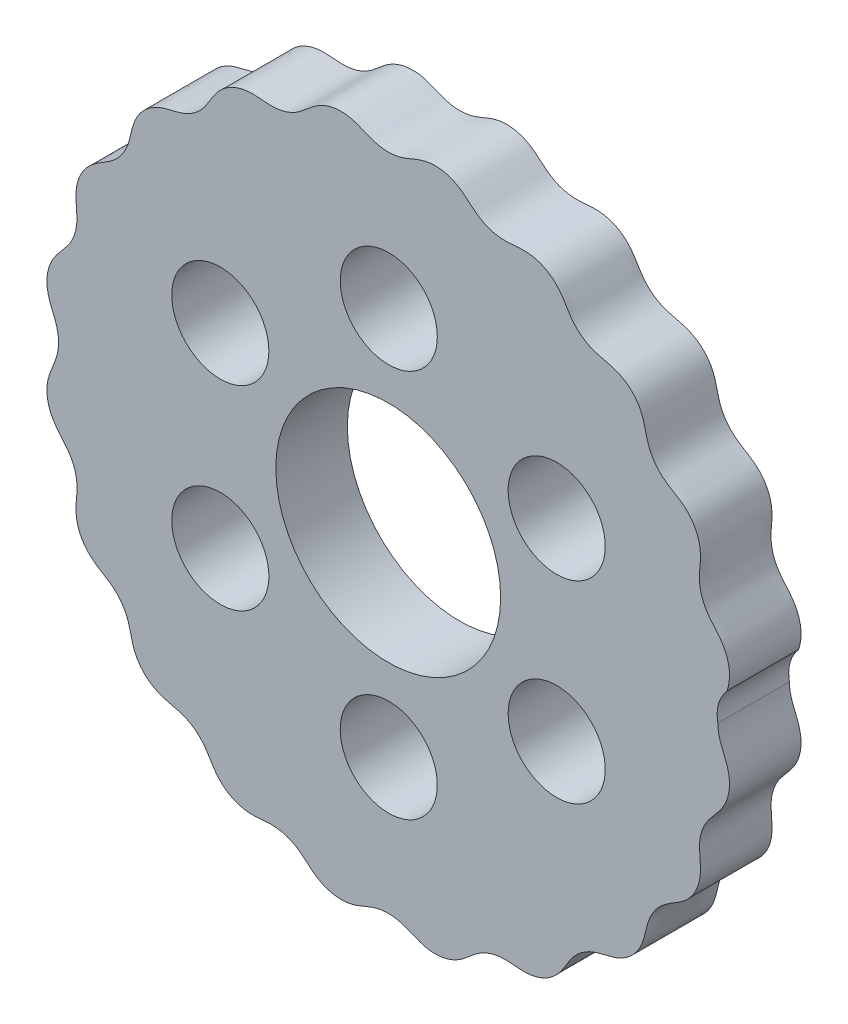
SolidWorks part; units mm, degrees
ref_plane "Front Plane" through (0, 0, 0) normal (0, 0, 1) x (1, 0, 0)
ref_plane "Top Plane" through (0, 0, 0) normal (0, 1, 0) x (1, 0, 0)
ref_plane "Right Plane" through (0, 0, 0) normal (1, 0, 0) x (0, 0, -1)
sketch "Sketch1" plane through (0, 0, 0) normal (0, 0, 1) x (1, 0, 0)
  spline S0 degree 4 poles (28.4232, 17.0994) (28.5775, 16.9984) (28.8791, 16.7867) (29.3025, 16.4267) (29.7783, 15.8595) (30.1762, 15.1774) (30.4555, 14.3878) (30.5822, 13.508) (30.5259, 12.5781) (30.4267, 11.6947) (30.4524, 10.841) (30.6166, 10.0442) (30.9061, 9.3262) (31.3279, 8.6403) (31.865, 8.0014) (32.4465, 7.3605) (32.9398, 6.604) (33.2503, 5.8126) (33.3942, 5.0292) (33.3985, 4.2869) (33.3069, 3.6905) (33.1661, 3.1943) (33.0172, 2.7916) (32.8858, 2.4743) (32.7509, 2.1586) (32.6212, 1.8407) (32.5187, 1.5581) (32.4421, 1.3122) (32.3869, 1.1049) (32.3484, 0.9372) (32.3158, 0.7683) (32.2895, 0.6004) (32.2695, 0.4318) (32.2562, 0.2498) (32.2495, 0.0634) (32.2494, -0.061) (32.2559, -0.2448) (32.2689, -0.4242) (32.2881, -0.5903) (32.3136, -0.7553) (32.3451, -0.9213) (32.3823, -1.0862) (32.4357, -1.2902) (32.51, -1.5322) (32.6096, -1.8103) (32.736, -2.1232) (32.8684, -2.4336) (32.9985, -2.745) (33.1477, -3.1396) (33.292, -3.6256) (33.3912, -4.2099) (33.4016, -4.9639) (33.2631, -5.784) (32.9336, -6.633) (32.3807, -7.4491) (31.7436, -8.1285) (31.1946, -8.8249) (30.792, -9.5638) (30.5426, -10.3176) (30.4261, -11.151) (30.4537, -12.0374) (30.5715, -12.9614) (30.549, -13.9461) (30.3058, -14.909) (29.8489, -15.7949) (29.1976, -16.5596) (28.3876, -17.1561) (27.551, -17.6113) (26.8095, -18.1374) (26.2056, -18.754) (25.7542, -19.4331) (25.4191, -20.211) (25.2057, -21.0593) (25.0232, -21.9462) (24.6789, -22.8243) (24.1554, -23.6109) (23.4726, -24.2662) (22.6632, -24.7596) (21.7674, -25.069) (20.8739, -25.2417) (20.0262, -25.4836) (19.258, -25.8528) (18.597, -26.3393) (18.0153, -26.9624) (17.5302, -27.6979) (17.088, -28.4937) (16.5078, -29.2435) (15.7729, -29.8593) (14.9126, -30.3026) (13.9653, -30.5464) (12.9803, -30.573) (12.0563, -30.4559) (11.17, -30.4252) (10.3361, -30.5384) (9.5813, -30.7844) (8.8407, -31.184) (8.1424, -31.7308) (7.4636, -32.3685) (6.65, -32.9246) (5.7398, -33.2826) (4.783, -33.428) (3.8265, -33.3603) (2.917, -33.0932) (2.0916, -32.709) (1.2664, -32.4001) (0.4293, -32.2392) (-0.3914, -32.2356) (-1.2297, -32.3897) (-2.0572, -32.6933) (-2.8817, -33.0786) (-3.7888, -33.3534) (-4.7338, -33.4284) (-5.6711, -33.298) (-6.5564, -32.9679) (-7.3502, -32.4586) (-8.0187, -31.8479) (-8.6907, -31.2877) (-9.4196, -30.8565) (-10.1845, -30.5737) (-11.0357, -30.4312) (-11.9448, -30.4426) (-12.8892, -30.5661) (-13.8952, -30.558) (-14.8711, -30.3206) (-15.7608, -29.8709) (-16.5224, -29.2335) (-17.1181, -28.4492) (-17.5657, -27.6324) (-18.0654, -26.8996) (-18.6505, -26.2948) (-19.2961, -25.8327) (-20.0567, -25.4727) (-20.9103, -25.2331) (-21.8252, -25.0577) (-22.7516, -24.7207) (-23.5731, -24.1899) (-24.2488, -23.4971) (-24.7514, -22.6804) (-25.0646, -21.786) (-25.2379, -20.8924) (-25.4769, -20.0441) (-25.8431, -19.2743) (-26.3266, -18.6112) (-26.9473, -18.027) (-27.6814, -17.5395) (-28.4775, -17.098) (-29.2296, -16.5212) (-29.8486, -15.7888) (-30.2958, -14.9305) (-30.5436, -13.9844) (-30.5746, -12.9992) (-30.4581, -12.0751) (-30.4244, -11.189) (-30.5343, -10.3547) (-30.7769, -9.5987) (-31.1736, -8.8566) (-31.7179, -8.1564) (-32.3561, -7.478) (-32.9154, -6.6671) (-33.2832, -5.7446) (-33.4325, -4.759) (-33.3534, -3.7577) (-33.0472, -2.7995) (-32.6379, -1.9396) (-32.3485, -1.0776) (-32.2237, -0.2236) (-32.2591, 0.591) (-32.4464, 1.417) (-32.7732, 2.2283) (-33.1464, 3.0535) (-33.3825, 3.9665) (-33.42, 4.9162) (-33.2475, 5.8577) (-32.8707, 6.7458) (-32.3063, 7.5334) (-31.6792, 8.2) (-31.1511, 8.8932) (-30.7677, 9.6235) (-30.5333, 10.3648) (-30.4259, 11.1826) (-30.4561, 12.053) (-30.5704, 12.9615) (-30.5495, 13.9308) (-30.3156, 14.8779) (-29.8754, 15.7519) (-29.2475, 16.5091) (-28.4654, 17.1083) (-27.649, 17.5564) (-26.9145, 18.0535) (-26.3073, 18.6361) (-25.8423, 19.2797) (-25.4793, 20.0388) (-25.2368, 20.8918) (-25.0622, 21.8067) (-24.7293, 22.7344) (-24.202, 23.5582) (-23.5123, 24.237) (-22.6978, 24.743) (-21.8045, 25.0602) (-20.911, 25.2342) (-20.062, 25.4704) (-19.2908, 25.8334) (-18.6255, 26.314) (-18.0388, 26.9323) (-17.5487, 27.665) (-17.108, 28.4612) (-16.5344, 29.2158) (-15.8129, 29.8307) (-14.9772, 30.2747) (-14.0665, 30.5266) (-13.125, 30.5795) (-12.2253, 30.4779) (-11.3523, 30.4206) (-10.5092, 30.5015) (-9.7246, 30.7236) (-8.9527, 31.1099) (-8.2248, 31.6544) (-7.5333, 32.3095) (-6.7137, 32.8928) (-5.7789, 33.275) (-4.7837, 33.4323) (-3.7766, 33.357) (-2.817, 33.0549) (-1.9569, 32.6456) (-1.0962, 32.3531) (-0.2427, 32.2248) (0.5721, 32.2565) (1.3989, 32.4406) (2.2113, 32.7652) (3.0356, 33.1397) (3.9476, 33.3797) (4.8916, 33.421) (5.8235, 33.2564) (6.6995, 32.8939) (7.4778, 32.353) (8.1429, 31.7319) (8.8357, 31.1869) (9.585, 30.7806) (10.3664, 30.5296) (11.2121, 30.4232) (12.0925, 30.4613) (12.9961, 30.5718) (13.9436, 30.5456) (14.8745, 30.3155) (15.74, 29.8824) (16.4956, 29.2614) (17.0984, 28.4817) (17.5471, 27.6655) (18.0416, 26.9294) (18.6219, 26.3199) (19.2633, 25.852) (20.021, 25.4859) (20.8733, 25.2405) (21.7882, 25.0666) (22.7171, 24.7378) (23.5432, 24.2141) (24.2251, 23.5274) (24.7346, 22.7151) (25.0556, 21.823) (25.2305, 20.9295) (25.4639, 20.0799) (25.8239, 19.3072) (26.3014, 18.6398) (26.9174, 18.0507) (27.6485, 17.5581) (28.4449, 17.1179) (29.2018, 16.5476) (29.8198, 15.8288) (30.2676, 14.9951) (30.5234, 14.0854) (30.5804, 13.144) (30.4802, 12.244) (30.4206, 11.3714) (30.498, 10.5278) (30.7169, 9.7426) (31.0994, 8.9686) (31.5675, 8.3403) (32.0384, 7.8191) (32.4373, 7.3378) (32.7245, 6.9278) (32.9672, 6.4897) (33.1591, 6.027) (33.2988, 5.5362) (33.3701, 5.0895) (33.3926, 4.696) (33.384, 4.3604) (33.3605, 4.0926) (33.3255, 3.8593) (33.2873, 3.6658) (33.2465, 3.4978) (33.2082, 3.3576) (33.169, 3.226) (33.1368, 3.1267) (33.0924, 2.9998) (33.0411, 2.8604) (32.9768, 2.6948) (32.8998, 2.5083) (32.7805, 2.2278) (32.6224, 1.8496) (32.4597, 1.4021) (32.3232, 0.8732) (32.2485, 0.3327) (32.241, -0.2135) (32.3014, -0.756) (32.425, -1.2874) (32.6016, -1.803) (32.8126, -2.3048) (33.0273, -2.8048) (33.2092, -3.3186) (33.3354, -3.8493) (33.3965, -4.3916) (33.3862, -5.1485) (33.224, -5.9318) (32.8893, -6.7001) (32.389, -7.4121) (31.9309, -7.9336) (31.4763, -8.458) (31.0772, -9.0284) (30.7021, -9.7701) (30.4438, -10.707) (30.4126, -11.8146) (30.5972, -13.0328) (30.5416, -13.9667) (30.3819, -14.5645) (30.2762, -14.8536) knots 0 0 0 0 0 0.002914 0.005828 0.008742 0.011656 0.015328 0.019 0.022672 0.026344 0.029388 0.032431 0.035474 0.038518 0.042063 0.045608 0.049154 0.052699 0.055413 0.058127 0.060842 0.062199 0.063556 0.064913 0.06627 0.067627 0.068984 0.069663 0.070342 0.07102 0.071699 0.072377 0.073056 0.073734 0.074413 0.07508 0.075747 0.076414 0.07708 0.077747 0.078414 0.079081 0.079748 0.081082 0.082416 0.083749 0.085083 0.086417 0.087751 0.090418 0.093086 0.095753 0.099621 0.103489 0.107357 0.111225 0.114347 0.117469 0.12059 0.123712 0.127579 0.131447 0.135314 0.139182 0.143133 0.147085 0.151036 0.154987 0.158193 0.161398 0.164603 0.167809 0.171509 0.17521 0.17891 0.182611 0.186333 0.190055 0.193777 0.197499 0.200725 0.20395 0.207176 0.210402 0.214124 0.217847 0.221569 0.225292 0.229159 0.233027 0.236895 0.240762 0.243884 0.247006 0.250127 0.253249 0.257117 0.260985 0.264852 0.26872 0.272443 0.276165 0.279887 0.28361 0.286836 0.290061 0.293287 0.296513 0.300235 0.303957 0.307679 0.311401 0.315101 0.318802 0.322502 0.326203 0.329408 0.332613 0.335819 0.339024 0.342976 0.346927 0.350878 0.35483 0.358697 0.362565 0.366432 0.3703 0.373421 0.376543 0.379664 0.382786 0.386654 0.390522 0.39439 0.398258 0.401981 0.405703 0.409425 0.413147 0.416373 0.419599 0.422824 0.42605 0.429772 0.433495 0.437217 0.440939 0.444807 0.448675 0.452543 0.456411 0.459532 0.462654 0.465776 0.468897 0.472765 0.476633 0.4805 0.484368 0.488319 0.49227 0.496222 0.500173 0.503378 0.506584 0.509789 0.512994 0.516695 0.520395 0.524096 0.527797 0.531603 0.535409 0.539216 0.543022 0.546079 0.549136 0.552193 0.555249 0.559056 0.562863 0.56667 0.570477 0.574345 0.578213 0.58208 0.585948 0.58907 0.592191 0.595313 0.598435 0.602303 0.60617 0.610038 0.613906 0.617628 0.621351 0.625073 0.628795 0.632021 0.635247 0.638473 0.641698 0.64542 0.649143 0.652865 0.656587 0.660287 0.663987 0.667688 0.671388 0.674594 0.677799 0.681005 0.68421 0.688161 0.692113 0.696064 0.700016 0.703967 0.707918 0.71187 0.715821 0.719027 0.722232 0.725438 0.728643 0.732343 0.736044 0.739744 0.743444 0.747166 0.750889 0.754611 0.758333 0.761558 0.764784 0.76801 0.771236 0.774958 0.77868 0.782403 0.786125 0.789993 0.793861 0.797729 0.801596 0.804718 0.80784 0.810961 0.814083 0.817951 0.821818 0.825686 0.829554 0.833276 0.836999 0.840721 0.844444 0.84767 0.850895 0.854121 0.857347 0.861069 0.864791 0.868513 0.872235 0.875935 0.879636 0.883336 0.887037 0.890242 0.893447 0.896653 0.899858 0.903809 0.905785 0.907761 0.909736 0.911712 0.913688 0.915663 0.917786 0.918847 0.919908 0.92097 0.922031 0.922562 0.923092 0.923623 0.924154 0.924692 0.92523 0.925768 0.926306 0.927383 0.928459 0.930612 0.932765 0.934918 0.93707 0.939223 0.941376 0.943527 0.945678 0.94783 0.949981 0.952132 0.954283 0.956434 0.958585 0.964071 0.966814 0.969557 0.9723 0.975043 0.977785 0.980528 0.985396 0.990264 0.995132 1 1 1 1 1 construction
  spline S1 degree 4 poles (32.25, 0) (32.25, -0.0358) (32.2511, -0.1076) (32.2559, -0.2448) (32.2689, -0.4242) (32.2881, -0.5903) (32.3136, -0.7553) (32.3451, -0.9213) (32.3823, -1.0862) (32.4357, -1.2902) (32.51, -1.5322) (32.6096, -1.8103) (32.736, -2.1232) (32.8684, -2.4336) (32.9985, -2.745) (33.1477, -3.1396) (33.292, -3.6256) (33.3912, -4.2099) (33.4016, -4.9639) (33.2631, -5.784) (32.9336, -6.633) (32.3807, -7.4491) (31.7436, -8.1285) (31.1946, -8.8249) (30.792, -9.5638) (30.5426, -10.3176) (30.4261, -11.151) (30.4537, -12.0374) (30.5715, -12.9614) (30.549, -13.9461) (30.3058, -14.909) (29.8489, -15.7949) (29.1976, -16.5596) (28.3876, -17.1561) (27.551, -17.6113) (26.8095, -18.1374) (26.2056, -18.754) (25.7542, -19.4331) (25.4191, -20.211) (25.2057, -21.0593) (25.0232, -21.9462) (24.6789, -22.8243) (24.1554, -23.6109) (23.4726, -24.2662) (22.6632, -24.7596) (21.7674, -25.069) (20.8739, -25.2417) (20.0262, -25.4836) (19.258, -25.8528) (18.597, -26.3393) (18.0153, -26.9624) (17.5302, -27.6979) (17.088, -28.4937) (16.5078, -29.2435) (15.7729, -29.8593) (14.9126, -30.3026) (13.9653, -30.5464) (12.9803, -30.573) (12.0563, -30.4559) (11.17, -30.4252) (10.3361, -30.5384) (9.5813, -30.7844) (8.8407, -31.184) (8.1424, -31.7308) (7.4636, -32.3685) (6.65, -32.9246) (5.7398, -33.2826) (4.783, -33.428) (3.8265, -33.3603) (2.917, -33.0932) (2.0916, -32.709) (1.2664, -32.4001) (0.4293, -32.2392) (-0.3914, -32.2356) (-1.2297, -32.3897) (-2.0572, -32.6933) (-2.8817, -33.0786) (-3.7888, -33.3534) (-4.7338, -33.4284) (-5.6711, -33.298) (-6.5564, -32.9679) (-7.3502, -32.4586) (-8.0187, -31.8479) (-8.6907, -31.2877) (-9.4196, -30.8565) (-10.1845, -30.5737) (-11.0357, -30.4312) (-11.9448, -30.4426) (-12.8892, -30.5661) (-13.8952, -30.558) (-14.8711, -30.3206) (-15.7608, -29.8709) (-16.5224, -29.2335) (-17.1181, -28.4492) (-17.5657, -27.6324) (-18.0654, -26.8996) (-18.6505, -26.2948) (-19.2961, -25.8327) (-20.0567, -25.4727) (-20.9103, -25.2331) (-21.8252, -25.0577) (-22.7516, -24.7207) (-23.5731, -24.1899) (-24.2488, -23.4971) (-24.7514, -22.6804) (-25.0646, -21.786) (-25.2379, -20.8924) (-25.4769, -20.0441) (-25.8431, -19.2743) (-26.3266, -18.6112) (-26.9473, -18.027) (-27.6814, -17.5395) (-28.4775, -17.098) (-29.2296, -16.5212) (-29.8486, -15.7888) (-30.2958, -14.9305) (-30.5436, -13.9844) (-30.5746, -12.9992) (-30.4581, -12.0751) (-30.4244, -11.189) (-30.5343, -10.3547) (-30.7769, -9.5987) (-31.1736, -8.8566) (-31.7179, -8.1564) (-32.3561, -7.478) (-32.9154, -6.6671) (-33.2832, -5.7446) (-33.4325, -4.759) (-33.3534, -3.7577) (-33.0472, -2.7995) (-32.6379, -1.9396) (-32.3485, -1.0776) (-32.2237, -0.2236) (-32.2591, 0.591) (-32.4464, 1.417) (-32.7732, 2.2283) (-33.1464, 3.0535) (-33.3825, 3.9665) (-33.42, 4.9162) (-33.2475, 5.8577) (-32.8707, 6.7458) (-32.3063, 7.5334) (-31.6792, 8.2) (-31.1511, 8.8932) (-30.7677, 9.6235) (-30.5333, 10.3648) (-30.4259, 11.1826) (-30.4561, 12.053) (-30.5704, 12.9615) (-30.5495, 13.9308) (-30.3156, 14.8779) (-29.8754, 15.7519) (-29.2475, 16.5091) (-28.4654, 17.1083) (-27.649, 17.5564) (-26.9145, 18.0535) (-26.3073, 18.6361) (-25.8423, 19.2797) (-25.4793, 20.0388) (-25.2368, 20.8918) (-25.0622, 21.8067) (-24.7293, 22.7344) (-24.202, 23.5582) (-23.5123, 24.237) (-22.6978, 24.743) (-21.8045, 25.0602) (-20.911, 25.2342) (-20.062, 25.4704) (-19.2908, 25.8334) (-18.6255, 26.314) (-18.0388, 26.9323) (-17.5487, 27.665) (-17.108, 28.4612) (-16.5344, 29.2158) (-15.8129, 29.8307) (-14.9772, 30.2747) (-14.0665, 30.5266) (-13.125, 30.5795) (-12.2253, 30.4779) (-11.3523, 30.4206) (-10.5092, 30.5015) (-9.7246, 30.7236) (-8.9527, 31.1099) (-8.2248, 31.6544) (-7.5333, 32.3095) (-6.7137, 32.8928) (-5.7789, 33.275) (-4.7837, 33.4323) (-3.7766, 33.357) (-2.817, 33.0549) (-1.9569, 32.6456) (-1.0962, 32.3531) (-0.2427, 32.2248) (0.5721, 32.2565) (1.3989, 32.4406) (2.2113, 32.7652) (3.0356, 33.1397) (3.9476, 33.3797) (4.8916, 33.421) (5.8235, 33.2564) (6.6995, 32.8939) (7.4778, 32.353) (8.1429, 31.7319) (8.8357, 31.1869) (9.585, 30.7806) (10.3664, 30.5296) (11.2121, 30.4232) (12.0925, 30.4613) (12.9961, 30.5718) (13.9436, 30.5456) (14.8745, 30.3155) (15.74, 29.8824) (16.4956, 29.2614) (17.0984, 28.4817) (17.5471, 27.6655) (18.0416, 26.9294) (18.6219, 26.3199) (19.2633, 25.852) (20.021, 25.4859) (20.8733, 25.2405) (21.7882, 25.0666) (22.7171, 24.7378) (23.5432, 24.2141) (24.2251, 23.5274) (24.7346, 22.7151) (25.0556, 21.823) (25.2305, 20.9295) (25.4639, 20.0799) (25.8239, 19.3072) (26.3014, 18.6398) (26.9174, 18.0507) (27.6485, 17.5581) (28.4449, 17.1179) (29.2018, 16.5476) (29.8198, 15.8288) (30.2676, 14.9951) (30.5234, 14.0854) (30.5804, 13.144) (30.4802, 12.244) (30.4206, 11.3714) (30.498, 10.5278) (30.7169, 9.7426) (31.0994, 8.9686) (31.5675, 8.3403) (32.0384, 7.8191) (32.4373, 7.3378) (32.7245, 6.9278) (32.9672, 6.4897) (33.1591, 6.027) (33.2988, 5.5362) (33.3701, 5.0895) (33.3926, 4.696) (33.384, 4.3604) (33.3605, 4.0926) (33.3255, 3.8593) (33.2873, 3.6658) (33.2465, 3.4978) (33.2082, 3.3576) (33.1789, 3.2592) (33.1617, 3.2045) (33.1529, 3.1773) knots 0.074413 0.074413 0.074413 0.074413 0.074413 0.07508 0.075747 0.076414 0.07708 0.077747 0.078414 0.079081 0.079748 0.081082 0.082416 0.083749 0.085083 0.086417 0.087751 0.090418 0.093086 0.095753 0.099621 0.103489 0.107357 0.111225 0.114347 0.117469 0.12059 0.123712 0.127579 0.131447 0.135314 0.139182 0.143133 0.147085 0.151036 0.154987 0.158193 0.161398 0.164603 0.167809 0.171509 0.17521 0.17891 0.182611 0.186333 0.190055 0.193777 0.197499 0.200725 0.20395 0.207176 0.210402 0.214124 0.217847 0.221569 0.225292 0.229159 0.233027 0.236895 0.240762 0.243884 0.247006 0.250127 0.253249 0.257117 0.260985 0.264852 0.26872 0.272443 0.276165 0.279887 0.28361 0.286836 0.290061 0.293287 0.296513 0.300235 0.303957 0.307679 0.311401 0.315101 0.318802 0.322502 0.326203 0.329408 0.332613 0.335819 0.339024 0.342976 0.346927 0.350878 0.35483 0.358697 0.362565 0.366432 0.3703 0.373421 0.376543 0.379664 0.382786 0.386654 0.390522 0.39439 0.398258 0.401981 0.405703 0.409425 0.413147 0.416373 0.419599 0.422824 0.42605 0.429772 0.433495 0.437217 0.440939 0.444807 0.448675 0.452543 0.456411 0.459532 0.462654 0.465776 0.468897 0.472765 0.476633 0.4805 0.484368 0.488319 0.49227 0.496222 0.500173 0.503378 0.506584 0.509789 0.512994 0.516695 0.520395 0.524096 0.527797 0.531603 0.535409 0.539216 0.543022 0.546079 0.549136 0.552193 0.555249 0.559056 0.562863 0.56667 0.570477 0.574345 0.578213 0.58208 0.585948 0.58907 0.592191 0.595313 0.598435 0.602303 0.60617 0.610038 0.613906 0.617628 0.621351 0.625073 0.628795 0.632021 0.635247 0.638473 0.641698 0.64542 0.649143 0.652865 0.656587 0.660287 0.663987 0.667688 0.671388 0.674594 0.677799 0.681005 0.68421 0.688161 0.692113 0.696064 0.700016 0.703967 0.707918 0.71187 0.715821 0.719027 0.722232 0.725438 0.728643 0.732343 0.736044 0.739744 0.743444 0.747166 0.750889 0.754611 0.758333 0.761558 0.764784 0.76801 0.771236 0.774958 0.77868 0.782403 0.786125 0.789993 0.793861 0.797729 0.801596 0.804718 0.80784 0.810961 0.814083 0.817951 0.821818 0.825686 0.829554 0.833276 0.836999 0.840721 0.844444 0.84767 0.850895 0.854121 0.857347 0.861069 0.864791 0.868513 0.872235 0.875935 0.879636 0.883336 0.887037 0.890242 0.893447 0.896653 0.899858 0.903809 0.905785 0.907761 0.909736 0.911712 0.913688 0.915663 0.917786 0.918847 0.919908 0.92097 0.922031 0.922562 0.923092 0.923623 0.924154 0.924154 0.924154 0.924154 0.924154
  spline S2 degree 2 poles (33.1529, 3.1773) (31.9223, 1.706) (32.25, 0) knots 0 0 0 1 1 1
extrude "Boss-Extrude1" add sketch "Sketch1" along normal blind 7
sketch "Sketch2" plane through (0, 0, 7) normal (0, 0, 1) x (1, 0, 0)
  line L0 (0, 0) -> (32.25, 0) construction
  line L1 (32.25, 0) -> (-32.25, 0) construction
  circle A1 centre (0, 0) radius 11
  circle A2 centre (0.0544, 18.9999) radius 4.75
  circle A3 centre (16.4816, 9.4528) radius 4.75
  circle A4 centre (-16.4272, 9.5471) radius 4.75
  circle A5 centre (16.4816, -9.4528) radius 4.75
  circle A6 centre (0.0544, -18.9999) radius 4.75
  circle A7 centre (-16.4272, -9.5471) radius 4.75
  spline S1 degree 4 poles (33.1529, 3.1773) (33.1617, 3.2045) (33.1789, 3.2592) (33.2082, 3.3576) (33.2465, 3.4978) (33.2873, 3.6658) (33.3255, 3.8593) (33.3605, 4.0926) (33.384, 4.3604) (33.3926, 4.696) (33.3701, 5.0895) (33.2988, 5.5362) (33.1591, 6.027) (32.9672, 6.4897) (32.7245, 6.9278) (32.4373, 7.3378) (32.0384, 7.8191) (31.5675, 8.3403) (31.0994, 8.9686) (30.7169, 9.7426) (30.498, 10.5278) (30.4206, 11.3714) (30.4802, 12.244) (30.5804, 13.144) (30.5234, 14.0854) (30.2676, 14.9951) (29.8198, 15.8288) (29.2018, 16.5476) (28.4449, 17.1179) (27.6485, 17.5581) (26.9174, 18.0507) (26.3014, 18.6398) (25.8239, 19.3072) (25.4639, 20.0799) (25.2305, 20.9295) (25.0556, 21.823) (24.7346, 22.7151) (24.2251, 23.5274) (23.5432, 24.2141) (22.7171, 24.7378) (21.7882, 25.0666) (20.8733, 25.2405) (20.021, 25.4859) (19.2633, 25.852) (18.6219, 26.3199) (18.0416, 26.9294) (17.5471, 27.6655) (17.0984, 28.4817) (16.4956, 29.2614) (15.74, 29.8824) (14.8745, 30.3155) (13.9436, 30.5456) (12.9961, 30.5718) (12.0925, 30.4613) (11.2121, 30.4232) (10.3664, 30.5296) (9.585, 30.7806) (8.8357, 31.1869) (8.1429, 31.7319) (7.4778, 32.353) (6.6995, 32.8939) (5.8235, 33.2564) (4.8916, 33.421) (3.9476, 33.3797) (3.0356, 33.1397) (2.2113, 32.7652) (1.3989, 32.4406) (0.5721, 32.2565) (-0.2427, 32.2248) (-1.0962, 32.3531) (-1.9569, 32.6456) (-2.817, 33.0549) (-3.7766, 33.357) (-4.7837, 33.4323) (-5.7789, 33.275) (-6.7137, 32.8928) (-7.5333, 32.3095) (-8.2248, 31.6544) (-8.9527, 31.1099) (-9.7246, 30.7236) (-10.5092, 30.5015) (-11.3523, 30.4206) (-12.2253, 30.4779) (-13.125, 30.5795) (-14.0665, 30.5266) (-14.9772, 30.2747) (-15.8129, 29.8307) (-16.5344, 29.2158) (-17.108, 28.4612) (-17.5487, 27.665) (-18.0388, 26.9323) (-18.6255, 26.314) (-19.2908, 25.8334) (-20.062, 25.4704) (-20.911, 25.2342) (-21.8045, 25.0602) (-22.6978, 24.743) (-23.5123, 24.237) (-24.202, 23.5582) (-24.7293, 22.7344) (-25.0622, 21.8067) (-25.2368, 20.8918) (-25.4793, 20.0388) (-25.8423, 19.2797) (-26.3073, 18.6361) (-26.9145, 18.0535) (-27.649, 17.5564) (-28.4654, 17.1083) (-29.2475, 16.5091) (-29.8754, 15.7519) (-30.3156, 14.8779) (-30.5495, 13.9308) (-30.5704, 12.9615) (-30.4561, 12.053) (-30.4259, 11.1826) (-30.5333, 10.3648) (-30.7677, 9.6235) (-31.1511, 8.8932) (-31.6792, 8.2) (-32.3063, 7.5334) (-32.8707, 6.7458) (-33.2475, 5.8577) (-33.42, 4.9162) (-33.3825, 3.9665) (-33.1464, 3.0535) (-32.7732, 2.2283) (-32.4464, 1.417) (-32.2591, 0.591) (-32.2237, -0.2236) (-32.3485, -1.0776) (-32.6379, -1.9396) (-33.0472, -2.7995) (-33.3534, -3.7577) (-33.4325, -4.759) (-33.2832, -5.7446) (-32.9154, -6.6671) (-32.3561, -7.478) (-31.7179, -8.1564) (-31.1736, -8.8566) (-30.7769, -9.5987) (-30.5343, -10.3547) (-30.4244, -11.189) (-30.4581, -12.0751) (-30.5746, -12.9992) (-30.5436, -13.9844) (-30.2958, -14.9305) (-29.8486, -15.7888) (-29.2296, -16.5212) (-28.4775, -17.098) (-27.6814, -17.5395) (-26.9473, -18.027) (-26.3266, -18.6112) (-25.8431, -19.2743) (-25.4769, -20.0441) (-25.2379, -20.8924) (-25.0646, -21.786) (-24.7514, -22.6804) (-24.2488, -23.4971) (-23.5731, -24.1899) (-22.7516, -24.7207) (-21.8252, -25.0577) (-20.9103, -25.2331) (-20.0567, -25.4727) (-19.2961, -25.8327) (-18.6505, -26.2948) (-18.0654, -26.8996) (-17.5657, -27.6324) (-17.1181, -28.4492) (-16.5224, -29.2335) (-15.7608, -29.8709) (-14.8711, -30.3206) (-13.8952, -30.558) (-12.8892, -30.5661) (-11.9448, -30.4426) (-11.0357, -30.4312) (-10.1845, -30.5737) (-9.4196, -30.8565) (-8.6907, -31.2877) (-8.0187, -31.8479) (-7.3502, -32.4586) (-6.5564, -32.9679) (-5.6711, -33.298) (-4.7338, -33.4284) (-3.7888, -33.3534) (-2.8817, -33.0786) (-2.0572, -32.6933) (-1.2297, -32.3897) (-0.3914, -32.2356) (0.4293, -32.2392) (1.2664, -32.4001) (2.0916, -32.709) (2.917, -33.0932) (3.8265, -33.3603) (4.783, -33.428) (5.7398, -33.2826) (6.65, -32.9246) (7.4636, -32.3685) (8.1424, -31.7308) (8.8407, -31.184) (9.5813, -30.7844) (10.3361, -30.5384) (11.17, -30.4252) (12.0563, -30.4559) (12.9803, -30.573) (13.9653, -30.5464) (14.9126, -30.3026) (15.7729, -29.8593) (16.5078, -29.2435) (17.088, -28.4937) (17.5302, -27.6979) (18.0153, -26.9624) (18.597, -26.3393) (19.258, -25.8528) (20.0262, -25.4836) (20.8739, -25.2417) (21.7674, -25.069) (22.6632, -24.7596) (23.4726, -24.2662) (24.1554, -23.6109) (24.6789, -22.8243) (25.0232, -21.9462) (25.2057, -21.0593) (25.4191, -20.211) (25.7542, -19.4331) (26.2056, -18.754) (26.8095, -18.1374) (27.551, -17.6113) (28.3876, -17.1561) (29.1976, -16.5596) (29.8489, -15.7949) (30.3058, -14.909) (30.549, -13.9461) (30.5715, -12.9614) (30.4537, -12.0374) (30.4261, -11.151) (30.5426, -10.3176) (30.792, -9.5638) (31.1946, -8.8249) (31.7436, -8.1285) (32.3807, -7.4491) (32.9336, -6.633) (33.2631, -5.784) (33.4016, -4.9639) (33.3912, -4.2099) (33.292, -3.6256) (33.1477, -3.1396) (32.9985, -2.745) (32.8684, -2.4336) (32.736, -2.1232) (32.6096, -1.8103) (32.51, -1.5322) (32.4357, -1.2902) (32.3823, -1.0862) (32.3451, -0.9213) (32.3136, -0.7553) (32.2881, -0.5903) (32.2689, -0.4242) (32.2559, -0.2448) (32.2511, -0.1076) (32.25, -0.0358) (32.25, 0) knots 0.074413 0.074413 0.074413 0.074413 0.074413 0.074944 0.075474 0.076005 0.076536 0.077597 0.078658 0.079719 0.080781 0.082903 0.084879 0.086855 0.08883 0.090806 0.092782 0.094757 0.098709 0.101914 0.105119 0.108325 0.11153 0.11523 0.118931 0.122632 0.126332 0.130054 0.133776 0.137498 0.14122 0.144446 0.147671 0.150897 0.154123 0.157845 0.161568 0.16529 0.169013 0.17288 0.176748 0.180616 0.184483 0.187605 0.190727 0.193849 0.19697 0.200838 0.204706 0.208574 0.212442 0.216164 0.219886 0.223609 0.227331 0.230557 0.233782 0.237008 0.240234 0.243956 0.247678 0.2514 0.255122 0.258823 0.262523 0.266223 0.269924 0.273129 0.276335 0.27954 0.282746 0.286697 0.290648 0.2946 0.298551 0.302502 0.306454 0.310405 0.314357 0.317562 0.320768 0.323973 0.327179 0.330879 0.334579 0.338279 0.34198 0.345702 0.349424 0.353146 0.356868 0.360094 0.36332 0.366545 0.369771 0.373494 0.377216 0.380938 0.384661 0.388528 0.392396 0.396264 0.400132 0.403254 0.406375 0.409497 0.412619 0.416486 0.420354 0.424222 0.428089 0.431896 0.435703 0.43951 0.443317 0.446374 0.449431 0.452488 0.455544 0.459351 0.463157 0.466964 0.47077 0.474471 0.478171 0.481872 0.485572 0.488778 0.491983 0.495188 0.498394 0.502345 0.506296 0.510247 0.514199 0.518066 0.521934 0.525802 0.529669 0.532791 0.535913 0.539034 0.542156 0.546024 0.549892 0.55376 0.557627 0.56135 0.565072 0.568794 0.572517 0.575742 0.578968 0.582194 0.58542 0.589142 0.592864 0.596586 0.600308 0.604176 0.608044 0.611912 0.615781 0.618902 0.622024 0.625145 0.628267 0.632135 0.636002 0.639869 0.643737 0.647688 0.65164 0.655591 0.659542 0.662748 0.665953 0.669159 0.672364 0.676064 0.679765 0.683465 0.687166 0.690888 0.69461 0.698332 0.702054 0.70528 0.708505 0.711731 0.714957 0.718679 0.722402 0.726124 0.729846 0.733714 0.737582 0.74145 0.745318 0.748439 0.751561 0.754683 0.757804 0.761672 0.76554 0.769407 0.773275 0.776998 0.78072 0.784443 0.788165 0.791391 0.794616 0.797842 0.801068 0.80479 0.808512 0.812234 0.815956 0.819656 0.823357 0.827057 0.830758 0.833963 0.837169 0.840374 0.843579 0.847531 0.851482 0.855433 0.859385 0.863252 0.86712 0.870987 0.874855 0.877976 0.881098 0.88422 0.887341 0.891209 0.895077 0.898945 0.902813 0.905481 0.908148 0.910816 0.91215 0.913483 0.914817 0.916151 0.917485 0.918819 0.919485 0.920152 0.920819 0.921486 0.922153 0.92282 0.923487 0.924154 0.924154 0.924154 0.924154 0.924154 construction
  dimension "D1" = 19
  dimension "D7" = 9.5
  dimension "D2" = 22
  dimension "D5" = 19
  dimension "D6" = 19
  dimension "D8" = 15.7684
extrude "Cut-Extrude3" cut sketch "Sketch2" against normal through all contours A1 | A7 | A4 | A2 | A3 | A5 | A6
